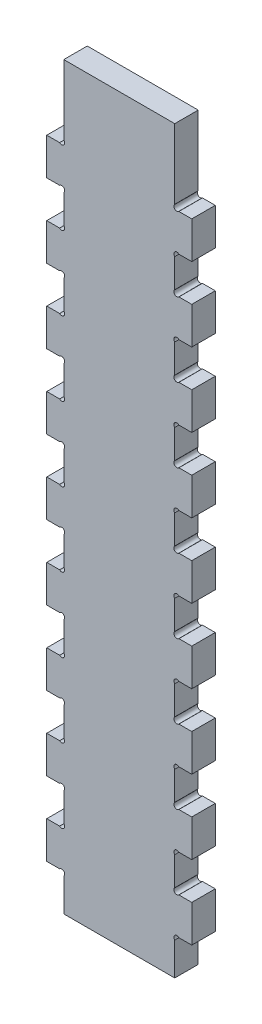
SolidWorks part; units mm, degrees
ref_plane "Front Plane" through (0, 0, 0) normal (0, 0, 1) x (1, 0, 0)
ref_plane "Top Plane" through (0, 0, 0) normal (0, 1, 0) x (1, 0, 0)
ref_plane "Right Plane" through (0, 0, 0) normal (1, 0, 0) x (0, 0, -1)
sketch "Sketch1" plane through (0, 0, 0) normal (0, 0, 1) x (1, 0, 0)
  line L1 (-14.9987, -100) -> (14.9987, -100)
  line L2 (-14.9987, -100) -> (-14.9987, 100)
  line L3 (-14.9987, 100) -> (14.9987, 100)
  line L4 (14.9987, -100) -> (14.9987, 100)
  line L5 (-14.9987, -100) -> (14.9987, 100) construction
  line L6 (-14.9987, 100) -> (14.9987, -100) construction
  point P0 (0, 0)
  dimension "D1" = 29.9974
  dimension "D2" = 200
extrude "Boss-Extrude1" add sketch "Sketch1" along normal blind 6.35
sketch "Sketch2" plane through (0, 0, 0) normal (0, 0, 1) x (1, 0, 0)
  line L0 (-14.9987, 100) -> (-14.9987, -100) construction
  line L1 (-14.9987, -80) -> (-19.5987, -80)
  line L2 (-14.9987, -80) -> (-14.9987, -90)
  line L3 (-14.9987, -90) -> (-19.5987, -90)
  line L4 (-19.5987, -80) -> (-19.5987, -90)
  line L6 (0, 100) -> (0, -101.8887) construction
  line L7 (14.9987, 100) -> (-14.9987, 100) construction
  line L8 (19.5987, -80) -> (19.5987, -90)
  line L9 (14.9987, -90) -> (19.5987, -90)
  line L10 (14.9987, -80) -> (14.9987, -90)
  line L11 (14.9987, -80) -> (19.5987, -80)
  line L12 (-14.9987, -100) -> (14.9987, -100) construction
  point P8 (-14.9987, -85)
  dimension "D2" = 4.6
  dimension "D3" = 10
  dimension "D1" = 10
extrude "Boss-Extrude2" add sketch "Sketch2" along normal blind 6.35
pattern_linear "LPattern1" count 9 spacing 20 along (0, 1, 0) of "Boss-Extrude2"
hole_wizard "dogBone01" positions "Sketch3" profile "Sketch4" hole size "1/16" standard "ANSI Inch" end condition through all
sketch "Sketch3" plane through (0, 0, 6.35) normal (0, 0, 1) x (1, 0, 0)
  line L0 (14.9987, -90) -> (16.1212, -90) construction
  line L1 (14.9987, -90) -> (14.9987, -91.1225) construction
  line L2 (14.9987, -90) -> (19.5987, -90) construction
  line L3 (0, 100) -> (0, -100) construction
  line L4 (14.9987, 100) -> (-14.9987, 100) construction
  line L5 (-14.9987, -100) -> (14.9987, -100) construction
  circle A0 centre (15.56, -90.5613) radius 0.7937
  point P8 (15.56, -90.5613)
  point P31 (-15.56, -90.5613)
  dimension "D1" = 1.5875
sketch "Sketch4" plane through (15.56, -90.5613, 6.35) normal (1, 0, 0) x (0, -1, 0)
  line L0 (0, 0) -> (0, 6.35)
  line L1 (0, 6.35) -> (0.7937, 6.35)
  line L2 (0.7937, 6.35) -> (0.7937, 0)
  line L5 (0.7937, 0) -> (0, 0)
  line L11 (0, -6.35) -> (0, 107.95) construction
  dimension "Thru Hole Dia." = 1.5875
  dimension "Thru Hole Depth" = 6.35
hole_wizard "dogBone02" positions "Sketch8" profile "Sketch9" hole size "1/16" standard "ANSI Inch" end condition through all
sketch "Sketch8" plane through (0, 0, 6.35) normal (0, 0, 1) x (1, 0, 0)
  line L0 (14.9987, -80) -> (14.9987, -78.8775) construction
  line L1 (14.9987, -80) -> (14.9987, -70) construction
  line L2 (14.9987, -80) -> (16.1212, -80) construction
  line L3 (19.5987, -80) -> (14.9987, -80) construction
  line L4 (0, 100) -> (0, -100) construction
  line L5 (14.9987, 100) -> (-14.9987, 100) construction
  line L6 (-14.9987, -100) -> (14.9987, -100) construction
  circle A0 centre (15.56, -79.4387) radius 0.7937
  point P1 (15.56, -79.4387)
  point P23 (-15.56, -79.4387)
  dimension "D1" = 1.5875
sketch "Sketch9" plane through (15.56, -79.4387, 6.35) normal (1, 0, 0) x (0, -1, 0)
  line L0 (0, 0) -> (0, 6.35)
  line L1 (0, 6.35) -> (0.7937, 6.35)
  line L2 (0.7937, 6.35) -> (0.7937, 0)
  line L5 (0.7937, 0) -> (0, 0)
  line L11 (0, -6.35) -> (0, 107.95) construction
  dimension "Thru Hole Dia." = 1.5875
  dimension "Thru Hole Depth" = 6.35
pattern_linear "LPattern2" count 9 spacing 20 along (0, 1, 0) of "dogBone01"
pattern_linear "LPattern4" count 9 spacing 20 along (0, 1, 0) of "dogBone02"
equation "\"z\"= 20cm"
equation "\"D2@Sketch1\"=\"z\""
equation "\"tWidth\"= 1cm"
equation "\"tHeight\"=0.182"
equation "\"D3@Sketch2\"=\"tWidth\""
equation "\"D1@Sketch2\"=\"tWidth\""
